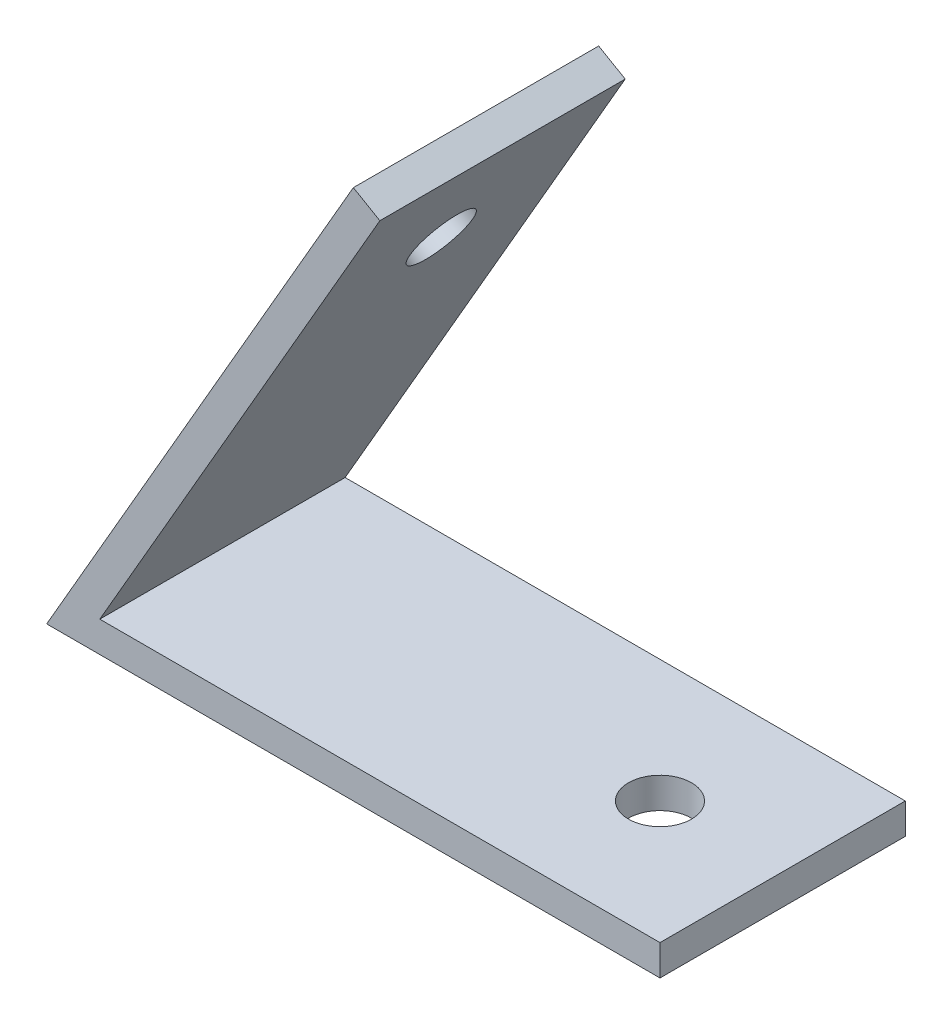
SolidWorks part; units mm, degrees
ref_plane "Front Plane" through (0, 0, 0) normal (0, 0, 1) x (1, 0, 0)
ref_plane "Top Plane" through (0, 0, 0) normal (0, 1, 0) x (1, 0, 0)
ref_plane "Right Plane" through (0, 0, 0) normal (1, 0, 0) x (0, 0, -1)
sketch "Sketch1" plane through (0, 0, 0) normal (0, 0, 1) x (1, 0, 0)
  line L0 (0, 0) -> (31.75, 0)
  line L1 (31.75, 0) -> (31.75, 1.5875)
  line L2 (2.7496, 1.5875) -> (31.75, 1.5875)
  line L3 (2.7496, 1.5875) -> (17.2498, 26.7026)
  line L4 (17.2498, 26.7026) -> (15.875, 27.4963)
  line L5 (15.875, 27.4963) -> (0, 0)
  dimension "D1" = 1.5875
  dimension "D2" = 1.5875
  dimension "D3" = 31.75
  dimension "D4" = 31.75
  dimension "D5" = 60
extrude "Boss-Extrude1" add sketch "Sketch1" along normal blind 12.7
hole_wizard "#4 Clearance Hole1" positions "3DSketch1" profile "Sketch3" hole size "#4" standard "ANSI Inch" end condition up to next
sketch3d "3DSketch1"
  line L0 (0, 0, 12.7) -> (0, 0, 0) construction
  line L1 (15.875, 27.4963, 12.7) -> (0, 0, 12.7) construction
  line L2 (0, 0, 12.7) -> (31.75, 0, 12.7) construction
  point P0 (12.7, 21.997, 6.35)
  point P2 (25.4, 0, 6.35)
  dimension "D1" = 25.4
  dimension "D2" = 25.4
  dimension "D3" = 6.35
  dimension "D4" = 6.35
sketch "Sketch3" plane through (12.7, 21.997, 6.35) normal (0, 0, 1) x (-0.5, -0.866, 0)
  line L0 (0, 0) -> (0, 1.5875)
  line L1 (0, 1.5875) -> (1.6319, 1.5875)
  line L2 (1.6319, 1.5875) -> (1.6319, 0)
  line L5 (1.6319, 0) -> (0, 0)
  line L11 (0, -6.35) -> (0, 107.95) construction
  dimension "Thru Hole Dia." = 3.2639
  dimension "Thru Hole Depth" = 1.5875
